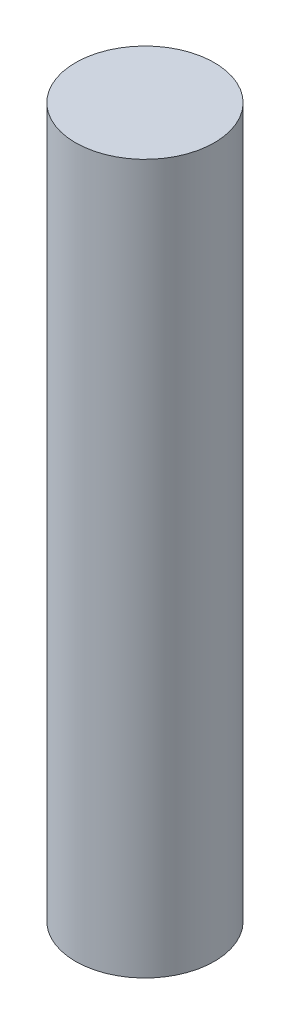
SolidWorks part; units mm, degrees
ref_plane "Front Plane" through (0, 0, 0) normal (0, 0, 1) x (1, 0, 0)
ref_plane "Top Plane" through (0, 0, 0) normal (0, 1, 0) x (1, 0, 0)
ref_plane "Right Plane" through (0, 0, 0) normal (1, 0, 0) x (0, 0, -1)
sketch "Sketch1" plane through (0, 0, 0) normal (0, 1, 0) x (1, 0, 0)
  circle A0 centre (0, 0) radius 2.35
  dimension "D1" = 4.7
extrude "Boss-Extrude1" add sketch "Sketch1" along normal blind 24
